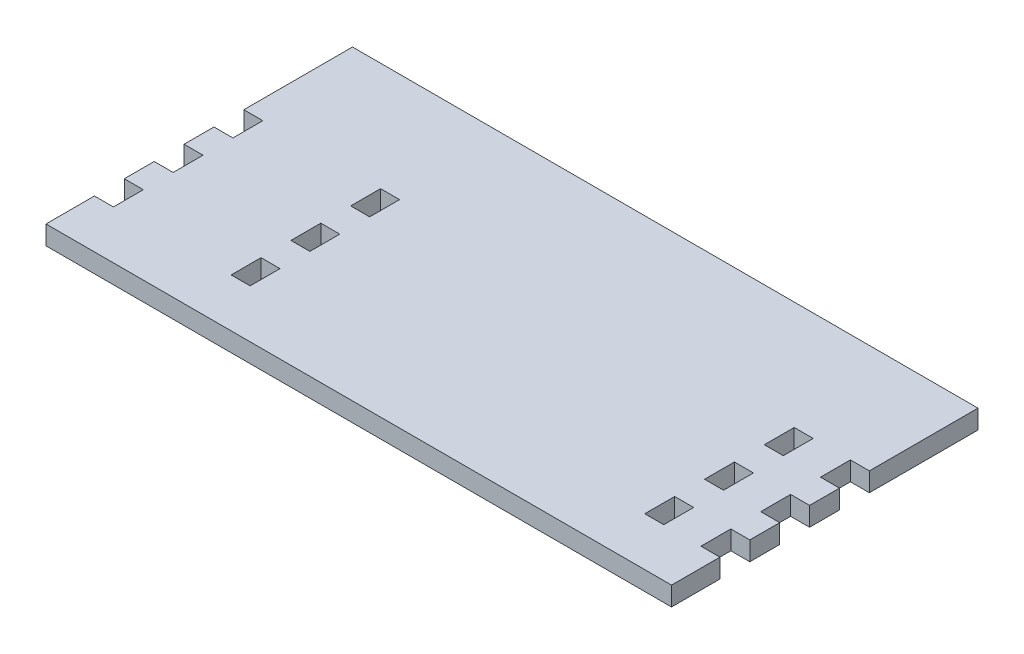
SolidWorks part; units mm, degrees
ref_plane "Front Plane" through (0, 0, 0) normal (0, 0, 1) x (1, 0, 0)
ref_plane "Top Plane" through (0, 0, 0) normal (0, 1, 0) x (1, 0, 0)
ref_plane "Right Plane" through (0, 0, 0) normal (1, 0, 0) x (0, 0, -1)
sketch "Sketch1" plane through (0, 0, 0) normal (0, 1, 0) x (1, 0, 0)
  line L0 (-104.648, -5) -> (-101.473, -5)
  line L1 (-3.175, 0) -> (-101.473, 0) construction
  line L2 (-78.599, -5) -> (-78.599, 0) construction
  line L3 (-3.175, -38.1) -> (-101.473, -38.1)
  line L4 (-104.648, -30) -> (-104.648, -38.1)
  line L5 (-3.175, -25) -> (-3.175, -30)
  line L6 (-104.648, -5) -> (-104.648, 0)
  line L7 (-104.648, 0) -> (-101.473, 0) construction
  line L8 (-104.648, -10) -> (-101.473, -10)
  line L9 (-3.175, -15) -> (-3.175, -20)
  line L10 (-3.175, -5) -> (-3.175, -10)
  line L11 (-101.473, -15) -> (-104.648, -15)
  line L12 (0, -20) -> (0, -25)
  line L13 (-104.648, -20) -> (-101.473, -20)
  line L14 (0, -10) -> (0, -15)
  line L15 (-101.473, -25) -> (-104.648, -25)
  line L16 (-104.648, -38.1) -> (-101.473, -38.1)
  line L17 (-104.648, -30) -> (-101.473, -30)
  line L18 (0, -30) -> (-3.175, -30)
  line L19 (-81.774, -5) -> (-78.599, -5)
  line L20 (0, -38.1) -> (-3.175, -38.1)
  line L21 (-52.324, 0) -> (-52.324, -38.1) construction
  line L22 (-3.175, 0) -> (0, 0) construction
  line L23 (0, 0) -> (0, -5) construction
  line L24 (-104.648, -10) -> (-104.648, -15)
  line L25 (-104.648, -20) -> (-104.648, -25)
  line L26 (-81.774, -5) -> (-81.774, -10)
  line L27 (-81.774, -10) -> (-78.599, -10)
  line L28 (0, -30) -> (-3.175, -30)
  line L29 (-3.175, -25) -> (0, -25)
  line L30 (-78.599, -5) -> (-78.599, -10)
  line L31 (0, -20) -> (-3.175, -20)
  line L32 (-81.774, -15) -> (-78.599, -15)
  line L33 (-3.175, -15) -> (0, -15)
  line L34 (-81.774, -15) -> (-81.774, -20)
  line L35 (-81.774, -20) -> (-78.599, -20)
  line L36 (0, -10) -> (-3.175, -10)
  line L37 (-78.599, -15) -> (-78.599, -20)
  line L38 (0, -5) -> (-3.175, -5)
  line L39 (-101.473, -5) -> (-101.473, -10)
  line L40 (-101.473, -15) -> (-101.473, -20)
  line L41 (-101.473, -25) -> (-101.473, -30)
  line L42 (-3.175, -25) -> (0, -25)
  line L43 (0, -20) -> (-3.175, -20)
  line L44 (-3.175, -15) -> (0, -15)
  line L45 (0, -10) -> (-3.175, -10)
  line L46 (0, 0) -> (-3.175, 0) construction
  line L47 (0, -5) -> (0, 0)
  line L48 (0, -30) -> (0, -38.1)
  line L49 (0, -5) -> (-3.175, -5)
  line L50 (-81.774, -25) -> (-78.599, -25)
  line L51 (-81.774, -25) -> (-81.774, -30)
  line L52 (-81.774, -30) -> (-78.599, -30)
  line L53 (-78.599, -25) -> (-78.599, -30)
  line L54 (-78.599, -10) -> (-78.599, -15) construction
  line L55 (-78.599, -20) -> (-78.599, -25) construction
  line L56 (-12.573, -20) -> (-12.573, -25) construction
  line L57 (-12.573, -10) -> (-12.573, -15) construction
  line L58 (-12.573, -5) -> (-12.573, 0) construction
  line L59 (-12.573, -25) -> (-12.573, -30)
  line L60 (-9.398, -30) -> (-12.573, -30)
  line L61 (-9.398, -25) -> (-9.398, -30)
  line L62 (-9.398, -25) -> (-12.573, -25)
  line L63 (-12.573, -15) -> (-12.573, -20)
  line L64 (-9.398, -20) -> (-12.573, -20)
  line L65 (-9.398, -15) -> (-9.398, -20)
  line L66 (-9.398, -15) -> (-12.573, -15)
  line L67 (-12.573, -5) -> (-12.573, -10)
  line L68 (-9.398, -10) -> (-12.573, -10)
  line L69 (-9.398, -5) -> (-9.398, -10)
  line L70 (-9.398, -5) -> (-12.573, -5)
  line L71 (-104.648, 0) -> (-104.648, 3.175)
  line L72 (-104.648, 3.175) -> (0, 3.175) construction
  line L73 (0, 3.175) -> (0, 0)
  line L75 (-104.648, 3.175) -> (0, 3.175) construction
  line L76 (-104.648, 3.175) -> (-104.648, 13.175)
  line L77 (-104.648, 13.175) -> (0, 13.175)
  line L78 (0, 3.175) -> (0, 13.175)
  dimension "D1" = 5
  dimension "D2" = 104.648
  dimension "D3" = 3.175
  dimension "D4" = 5
  dimension "D5" = 38.1
  dimension "D6" = 5
  dimension "D7" = 5
  dimension "D8" = 3.175
  dimension "D9" = 19.699
  dimension "D10" = 3.175
  dimension "D11" = 10
extrude "Boss-Extrude1" add sketch "Sketch1" along normal blind 3.175 contours L48 L18 L5 L29 L12 L31 L9 L33 L14 L36 L10 L38 L47 L46 L1 L7 L6 L0 L39 L8 L24 L11 L40 L13 L25 L15 L41 L17 L4 L16 L3 L20
